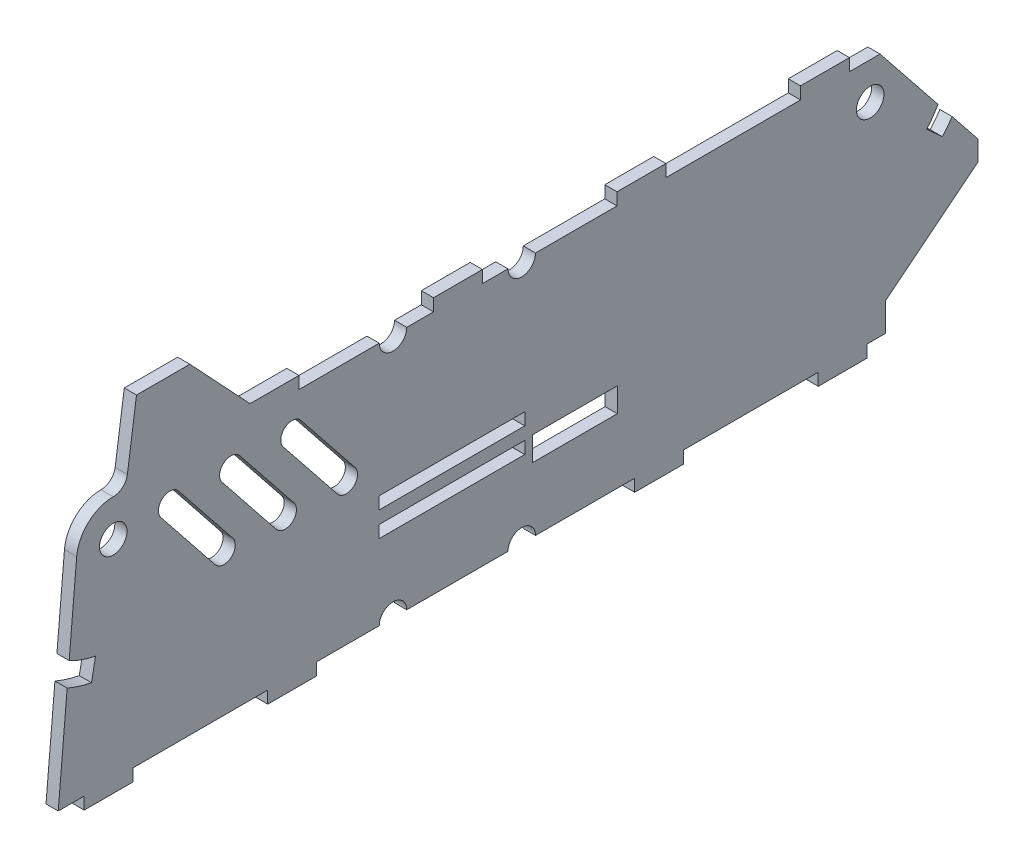
SolidWorks part; units mm, degrees
ref_plane "前视基准面" through (0, 0, 0) normal (0, 0, 1) x (1, 0, 0)
ref_plane "上视基准面" through (0, 0, 0) normal (0, 1, 0) x (1, 0, 0)
ref_plane "右视基准面" through (0, 0, 0) normal (1, 0, 0) x (0, 0, -1)
sketch "右侧结构" plane through (0, 0, 0) normal (1, 0, 0) x (0, 0, -1)
  line L0 (-44.2613, 14.3381) -> (-20.3822, 14.3381)
  line L1 (-96.6617, 0) -> (38.5883, 0)
  line L6 (-44.2613, 18.3959) -> (-20.3822, 18.3959)
  line L8 (-44.2613, 18.3959) -> (-44.2613, 16.3959)
  line L9 (-44.2613, 12.3381) -> (-20.3822, 12.3381)
  line L10 (-20.3822, 12.3381) -> (-20.3822, 14.3381)
  line L11 (-44.2613, 16.3959) -> (-20.3822, 16.3959)
  line L12 (-44.2613, 14.3381) -> (-44.2613, 12.3381)
  line L13 (-20.3822, 16.3959) -> (-20.3822, 18.3959)
  line L16 (-19.1356, 10.5554) -> (-5.2617, 10.5554)
  line L17 (-5.2617, 10.5554) -> (-5.2617, 14.5)
  line L18 (-5.2617, 14.5) -> (-19.1356, 14.5)
  line L19 (-19.1356, 14.5) -> (-19.1356, 10.5554)
  line L20 (-98.4315, 34.3169) -> (-88.4315, 34.3169) construction
  line L21 (36.0883, 34) -> (47.8781, 23.2124) construction
  line L22 (37.6933, 40) -> (-87.6642, 40)
  line L23 (-93.6414, 34.5229) -> (-96.6617, 0) construction
  line L25 (38.5883, 0) -> (38.5883, 38.8804) construction
  line L26 (38.5883, 38.8804) -> (37.6933, 40) construction
  line L36 (45.3288, 25.545) -> (47.8781, 23.2124)
  line L39 (-87.6642, 34) -> (-91.2196, 15.4465) construction
  line L42 (-90.5609, 18.8839) -> (-91.2196, 15.4465)
  line L45 (-93.6414, 34.5229) -> (-94.8767, 20.4034)
  line L48 (-49.5684, 23.2124) -> (-58.4315, 34.3169) construction
  line L49 (-51.0148, 22.058) -> (-59.8778, 33.1625)
  line L50 (-48.1221, 24.3668) -> (-56.9851, 35.4713)
  line L51 (-59.5684, 23.2124) -> (-68.4315, 34.3169) construction
  line L52 (-61.0148, 22.058) -> (-69.8778, 33.1625)
  line L53 (-58.1221, 24.3668) -> (-66.9851, 35.4713)
  line L54 (-69.5684, 23.2124) -> (-78.4315, 34.3169) construction
  line L55 (-71.0148, 22.058) -> (-79.8778, 33.1625)
  line L56 (-68.1221, 24.3668) -> (-76.9851, 35.4713)
  line L57 (38.5883, 38.8804) -> (53.7082, 19.9645) construction
  line L60 (53.7082, 19.9645) -> (53.7082, 16.7131)
  line L66 (38.5883, 4.6274) -> (38.5883, 0)
  line L69 (-88.4315, 34.3169) -> (-78.4315, 34.3169) construction
  line L70 (-78.4315, 34.3169) -> (-68.4315, 34.3169) construction
  line L71 (-68.4315, 34.3169) -> (-58.4315, 34.3169) construction
  line L72 (-58.4315, 34.3169) -> (-48.4315, 34.3169) construction
  line L73 (-48.4315, 34.3169) -> (-38.4315, 34.3169) construction
  line L74 (-38.4315, 34.3169) -> (-28.4315, 34.3169) construction
  line L75 (-28.4315, 34.3169) -> (-18.4315, 34.3169) construction
  line L76 (-18.4315, 34.3169) -> (-8.4315, 34.3169) construction
  line L77 (-8.4315, 34.3169) -> (1.5685, 34.3169) construction
  line L78 (1.5685, 34.3169) -> (11.5685, 34.3169) construction
  line L88 (37.6933, 40) -> (47.164, 28.1517)
  line L91 (-96.6304, 6.9377) -> (-86.6239, 6.9377) construction
  line L92 (-86.6239, 6.9377) -> (-76.6175, 6.9377) construction
  line L93 (-76.6175, 6.9377) -> (-66.611, 6.9377) construction
  line L94 (-66.611, 6.9377) -> (-56.6046, 6.9377) construction
  line L95 (-56.6046, 6.9377) -> (-46.5981, 6.9377) construction
  line L96 (-46.5981, 6.9377) -> (-36.5917, 6.9377) construction
  line L97 (42.0237, 22.9708) -> (34.3307, 32.5952) construction
  line L98 (-16.5788, 6.9377) -> (-6.5723, 6.9377) construction
  line L99 (-6.5723, 6.9377) -> (3.4341, 6.9377) construction
  line L100 (3.4341, 6.9377) -> (13.4406, 6.9377) construction
  line L101 (13.4406, 6.9377) -> (23.447, 6.9377) construction
  line L102 (23.447, 6.9377) -> (33.4534, 6.9377) construction
  line L105 (-36.5917, 6.9377) -> (-26.5852, 6.9377) construction
  line L106 (-26.5852, 6.9377) -> (-16.5788, 6.9377) construction
  line L107 (49.4706, 25.266) -> (53.7082, 19.9645)
  line L108 (53.7082, 16.7131) -> (38.5883, 4.6274)
  line L109 (42.0237, 22.9708) -> (44.209, 20.2369) construction
  line L110 (-95.2026, 16.6781) -> (-96.6617, 0)
  arc A0 (-87.6642, 40) -> (-93.6414, 34.5229) centre (-87.6642, 34) ccw
  arc A15 (-51.0148, 22.058) -> (-48.1221, 24.3668) centre (-49.5684, 23.2124) ccw
  arc A16 (-56.9851, 35.4713) -> (-59.8778, 33.1625) centre (-58.4315, 34.3169) ccw
  arc A17 (-61.0148, 22.058) -> (-58.1221, 24.3668) centre (-59.5684, 23.2124) ccw
  arc A18 (-66.9851, 35.4713) -> (-69.8778, 33.1625) centre (-68.4315, 34.3169) ccw
  arc A19 (-71.0148, 22.058) -> (-68.1221, 24.3668) centre (-69.5684, 23.2124) ccw
  arc A20 (-76.9851, 35.4713) -> (-79.8778, 33.1625) centre (-78.4315, 34.3169) ccw
  circle A21 centre (36.0883, 34) radius 2.25
  arc A23 (47.164, 28.1517) -> (42.0237, 22.9708) centre (36.0883, 34) cw construction
  arc A24 (49.4706, 25.266) -> (44.209, 20.2369) centre (36.0883, 34) cw construction
  arc A25 (47.164, 28.1517) -> (45.3288, 25.545) centre (36.0883, 34) cw
  arc A28 (49.4706, 25.266) -> (47.8781, 23.2124) centre (36.0883, 34) cw
  circle A31 centre (-87.6642, 34) radius 2.25
  arc A32 (-94.8767, 20.4034) -> (-90.5609, 18.8839) centre (-87.6642, 34) ccw
  arc A33 (-95.2026, 16.6781) -> (-91.2196, 15.4465) centre (-87.6642, 34) ccw
  arc A34 (-44.1822, 40) -> (-39.6822, 40) centre (-41.9322, 40) ccw
  arc A35 (-23.1322, 40) -> (-18.6322, 40) centre (-20.8822, 40) ccw
  arc A37 (-44.1822, 0) -> (-39.6822, 0) centre (-41.9322, 0) cw
  arc A38 (-23.1322, 0) -> (-18.6322, 0) centre (-20.8822, 0) cw
  point P42 (-12.1221, 40)
  point P45 (0, 0)
  point P49 (0, 0)
  point P55 (0, 0)
  point P56 (0, 0)
  point P57 (0, 0)
  point P58 (0, 0)
  point P59 (0, 0)
  point P60 (0, 0)
  point P61 (-25.7875, 40)
  point P62 (0, 0)
  point P63 (-21.7256, 0)
  point P64 (0, 0)
  point P76 (-53.9999, 28.7647)
  point P83 (-63.9999, 28.7647)
  point P90 (-73.9999, 28.7647)
  dimension "D1" = 6
  dimension "D3" = 12.3381
  dimension "D11" = 135.25
  dimension "D13" = 4.5
  dimension "D14" = 6
  dimension "D19" = 3.5
  dimension "D20" = 2.25
  dimension "D2" = 40
  dimension "D4" = 1.7827
  dimension "D5" = 3.9446
  dimension "D6" = 23.8791
  dimension "D7" = 13.8739
  dimension "D8" = 1.2466
  dimension "D9" = 2.0578
  dimension "D10" = 2
  dimension "D12" = 85
  dimension "D15" = 43.85
  dimension "D16" = 3.5
  dimension "D17" = 5
  dimension "D18" = 2.5
  dimension "D21" = 21.55
  dimension "D22" = 0.5
extrude "凸台-拉伸1" add sketch "右侧结构" along normal blind 2
sketch "草图2" plane through (0, 0, 0) normal (1, 0, 0) x (0, 0, -1)
  line L0 (35.5883, 0) -> (35.5883, -2)
  line L1 (-83.8627, 52.5) -> (-85.359, 42)
  line L2 (35.5883, -2) -> (27.5883, -2)
  line L3 (27.5883, -2) -> (27.5883, 0)
  line L4 (27.5883, 0) -> (35.5883, 0)
  line L5 (-83.8627, 52.5) -> (-75.1391, 52.5)
  line L6 (-2.4117, 0) -> (5.5883, 0)
  line L7 (5.5883, 0) -> (5.5883, -2)
  line L8 (5.5883, -2) -> (-2.4117, -2)
  line L9 (-2.4117, -2) -> (-2.4117, 0)
  line L10 (-32.4117, 0) -> (-24.4117, 0) construction
  line L11 (-24.4117, 0) -> (-24.4117, -2) construction
  line L12 (-24.4117, -2) -> (-32.4117, -2) construction
  line L13 (-32.4117, -2) -> (-32.4117, 0) construction
  line L14 (-62.4117, 0) -> (-54.4117, 0)
  line L15 (-54.4117, 0) -> (-54.4117, -2)
  line L16 (-54.4117, -2) -> (-62.4117, -2)
  line L17 (-62.4117, -2) -> (-62.4117, 0)
  line L18 (-92.4117, 0) -> (-84.4117, 0)
  line L19 (-84.4117, 0) -> (-84.4117, -2)
  line L20 (-84.4117, -2) -> (-92.4117, -2)
  line L21 (-92.4117, -2) -> (-92.4117, 0)
  line L22 (32.6933, 42) -> (32.6933, 40)
  line L23 (32.6933, 40) -> (24.6933, 40)
  line L24 (24.6933, 40) -> (24.6933, 42)
  line L25 (24.6933, 42) -> (32.6933, 42)
  line L26 (-75.1391, 52.5) -> (-65.3067, 42)
  line L27 (2.6933, 42) -> (2.6933, 40)
  line L28 (2.6933, 40) -> (-5.3067, 40)
  line L29 (-5.3067, 40) -> (-5.3067, 42)
  line L30 (-5.3067, 42) -> (2.6933, 42)
  line L31 (-27.3067, 42) -> (-27.3067, 40)
  line L32 (-27.3067, 40) -> (-35.3067, 40)
  line L33 (-35.3067, 40) -> (-35.3067, 42)
  line L34 (-35.3067, 42) -> (-27.3067, 42)
  line L35 (-57.3067, 42) -> (-57.3067, 40)
  line L36 (-57.3067, 40) -> (-65.3067, 40)
  line L37 (-65.3067, 40) -> (-65.3067, 42) construction
  line L38 (-65.3067, 42) -> (-57.3067, 42)
  line L39 (38.5883, 4.6274) -> (38.5883, 0) construction
  line L40 (-18.6322, 0) -> (38.5883, 0) construction
  line L41 (37.6933, 40) -> (-18.6322, 40) construction
  line L42 (-87.6642, 40) -> (-65.3067, 40)
  arc A0 (-87.6642, 40) -> (-85.359, 42) centre (-87.6642, 42.3285) ccw
  dimension "D1" = 3
  dimension "D2" = 2
  dimension "D3" = 8
  dimension "D5" = 2
  dimension "D6" = 8
  dimension "D7" = 5
  dimension "D9" = 12.5
  dimension "D4" = 5
  dimension "D8" = 4
extrude "上下板接口" add sketch "草图2" along normal up to surface (2 mm away) from surface at 0 up to face at (2, 34, 85.4142) starting at face at (0, 34, 85.4142)
